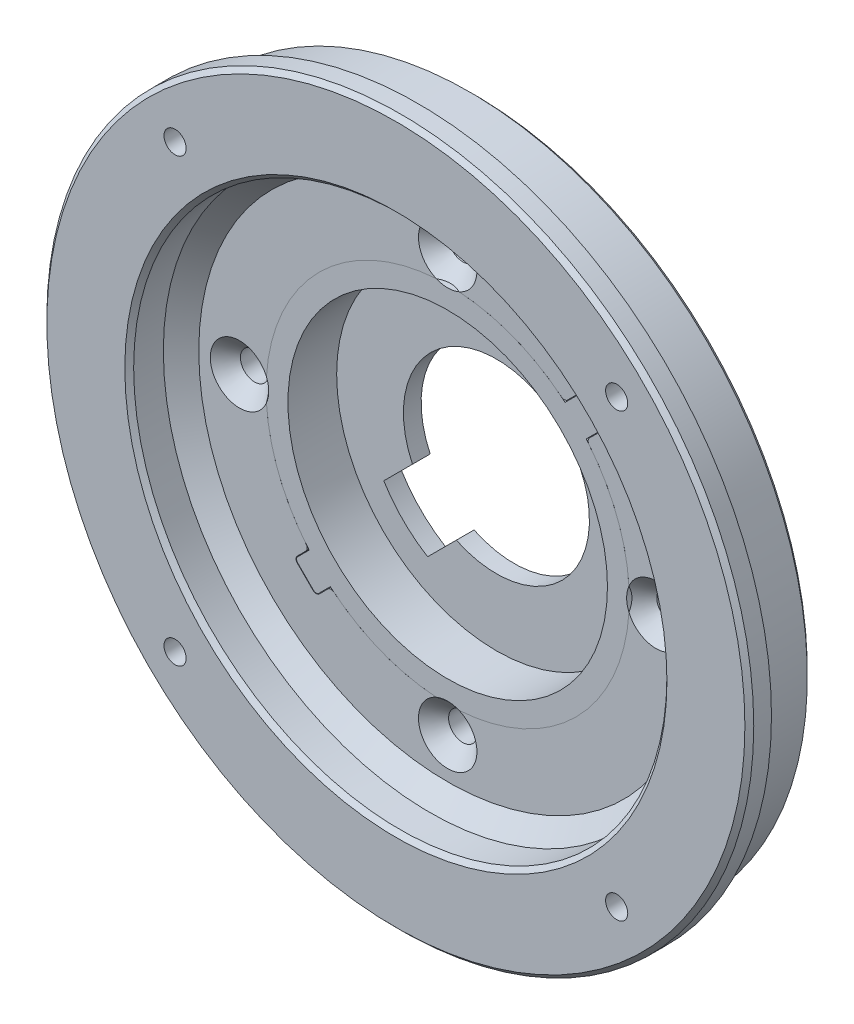
SolidWorks part; units mm, degrees
material "POM 乙缩醛共聚物"
ref_plane "前视基准面" through (0, 0, 0) normal (0, 0, 1) x (1, 0, 0)
ref_plane "上视基准面" through (0, 0, 0) normal (0, 1, 0) x (1, 0, 0)
ref_plane "右视基准面" through (0, 0, 0) normal (1, 0, 0) x (0, 0, -1)
sketch "草图1" plane through (0, 0, 0) normal (0, 0, 1) x (1, 0, 0)
  circle A0 centre (0, 0) radius 30.1
  circle A1 centre (0, 0) radius 38.1
  dimension "D1" = 8
  dimension "D2" = 76.2
extrude "凸台-拉伸1" add sketch "草图1" along normal blind 3.35
sketch "草图2" plane through (0, 0, 3.35) normal (0, 0, 1) x (1, 0, 0)
  circle A0 centre (0, 0) radius 30.1 construction
  circle A1 centre (0, 0) radius 30.1
  circle A2 centre (0, 0) radius 39.9
  circle A3 centre (0, 0) radius 38.1 construction
  dimension "D1" = 1.8
extrude "凸台-拉伸2" add sketch "草图2" along normal blind 2.5
sketch "草图4" plane through (0, 0, 0) normal (0, 0, -1) x (-1, 0, 0)
  circle A0 centre (0, 0) radius 20.5
  circle A1 centre (0, 0) radius 38.1 construction
  circle A2 centre (0, 0) radius 38.1
  dimension "D1" = 41
extrude "凸台-拉伸3" add sketch "草图4" along normal blind 3
chamfer "倒角1" distance 2 angle 45 1 edges at (30.1, 0, 0)
sketch "草图5" plane through (0, 0, 0) normal (0, 0, 1) x (1, 0, 0)
  line L0 (0, 0) -> (-23.5, 0) construction
  circle A0 centre (0, 0) radius 23.5 construction
  circle A1 centre (-23.5, 0) radius 1.5
  circle A2 centre (0, 23.5) radius 1.5
  circle A3 centre (23.5, 0) radius 1.5
  circle A4 centre (0, -23.5) radius 1.5
  point P13 (0, 0)
  dimension "D1" = 47
  dimension "D2" = 3
  dimension "D3" = 4
extrude "切除-拉伸1" cut sketch "草图5" against normal blind 10
chamfer "倒角2" distance 0.5 angle 45 2 edges at (39.9, 0, 5.85) (30.1, 0, 5.85)
sketch "草图6" plane through (0, 0, -3) normal (0, 0, -1) x (-1, 0, 0)
  circle A0 centre (0, 0) radius 20.5 construction
  circle A1 centre (0, 0) radius 20.5
  circle A2 centre (23.5, 0) radius 1.5 construction
  circle A3 centre (0, 23.5) radius 1.5 construction
  circle A4 centre (-23.5, 0) radius 1.5 construction
  circle A5 centre (0, -23.5) radius 1.5 construction
  circle A6 centre (23.5, 0) radius 1.5
  circle A7 centre (0, 23.5) radius 1.5
  circle A8 centre (-23.5, 0) radius 1.5
  circle A9 centre (0, -23.5) radius 1.5
  circle A10 centre (0, 0) radius 29.5
  dimension "D1" = 59
extrude "凸台-拉伸4" add sketch "草图6" along normal blind 5.5
chamfer "倒角3" distance 3 angle 45 1 edges at (-29.5, 0, -3)
chamfer "倒角4" distance 0.5 angle 45 1 edges at (-38.1, 0, -3)
hole_wizard "打孔尺寸(%根据十字)槽半沉头木螺钉的类型1" positions "3D草图1" profile "草图7" countersink size "M3" standard "GB"
sketch3d "3D草图1"
  line L0 (23.5, 0, -8.5) -> (23.5, 0, 0) construction
  line L1 (0, -23.5, -8.5) -> (0, -23.5, 0) construction
  line L2 (-23.5, 0, -8.5) -> (-23.5, 0, 0) construction
  line L3 (0, 23.5, -8.5) -> (0, 23.5, 0) construction
  point P0 (23.5, 0, 0)
  point P4 (0, -23.5, 0)
  point P8 (-23.5, 0, 0)
  point P12 (0, 23.5, 0)
sketch "草图7" plane through (23.5, 0, 0) normal (1, 0, 0) x (0, -1, 0)
  line L0 (0, 0) -> (0, 13.4614)
  line L1 (0, 13.4614) -> (1.6, 12.5)
  line L2 (1.6, 12.5) -> (1.6, 1.7)
  line L3 (1.6, 1.7) -> (3.3, 0)
  line L5 (3.3, 0) -> (0, 0)
  line L6 (-1.6, 1.7) -> (-3.3, 0) construction
  line L10 (0, 13.4614) -> (-1.6, 12.5) construction
  line L11 (0, -6.35) -> (0, 107.95) construction
  dimension "孔直径" = 3.2
  dimension "孔深度" = 12.5
  dimension "近端锥形沉头孔直径" = 6.6
  dimension "近端锥形沉头孔角度" = 90
  dimension "导头角度" = 118
sketch "草图8" plane through (0, 0, -3) normal (0, 0, -1) x (-1, 0, 0)
  line L0 (0, 0) -> (-24.9255, -24.9255) construction
  line L1 (0, 0) -> (0, -35.25) construction
  circle A0 centre (0, 0) radius 35.25 construction
  circle A1 centre (-24.9255, -24.9255) radius 1.2
  circle A2 centre (-24.9255, 24.9255) radius 1.2
  circle A3 centre (24.9255, 24.9255) radius 1.2
  circle A4 centre (24.9255, -24.9255) radius 1.2
  point P14 (0, 0)
  dimension "D1" = 70.5
  dimension "D3" = 2.4
  dimension "D2" = 45
  dimension "D4" = 4
extrude "切除-拉伸2" cut sketch "草图8" against normal blind 10
hole_wizard "M3 螺纹孔1" positions "3D草图2" profile "草图9" tap size "M3" standard "GB"
sketch3d "3D草图2"
  line L0 (24.9255, 24.9255, 5.85) -> (24.9255, 24.9255, -3) construction
  line L1 (24.9255, -24.9255, 5.85) -> (24.9255, -24.9255, -3) construction
  line L2 (-24.9255, -24.9255, 5.85) -> (-24.9255, -24.9255, -3) construction
  line L3 (-24.9255, 24.9255, 5.85) -> (-24.9255, 24.9255, -3) construction
  point P0 (24.9255, 24.9255, 5.85)
  point P4 (24.9255, -24.9255, 5.85)
  point P8 (-24.9255, -24.9255, 5.85)
  point P12 (-24.9255, 24.9255, 5.85)
sketch "草图9" plane through (24.9255, 24.9255, 5.85) normal (1, 0, 0) x (0, -1, 0)
  line L0 (0, 0) -> (0, 13.2511)
  line L1 (0, 13.2511) -> (1.25, 12.5)
  line L2 (1.25, 12.5) -> (1.25, 0)
  line L5 (1.25, 0) -> (0, 0)
  line L10 (0, 13.2511) -> (-1.25, 12.5) construction
  line L11 (0, -6.35) -> (0, 107.95) construction
  dimension "螺纹孔钻头直径" = 2.5
  dimension "螺纹孔钻头深度" = 12.5
  dimension "导头角度" = 118
cosmetic thread "孔螺蚊线1" parameters "D1"=8.85, "D2"=3
cosmetic thread "孔螺蚊线2" parameters "D1"=8.85, "D2"=3
cosmetic thread "孔螺蚊线3" parameters "D1"=8.85, "D2"=3
cosmetic thread "孔螺蚊线4" parameters "D1"=8.85, "D2"=3
sketch "草图12" plane through (0, 0, 0) normal (0, 0, 1) x (1, 0, 0)
  line L0 (-14.4957, -14.4957) -> (14.4957, 14.4957) construction
  line L1 (0, 0) -> (20.5, 0) construction
  line L2 (16.0867, 16.0867) -> (12.9047, 12.9047) construction
  line L3 (17.3241, 14.8492) -> (14.1421, 11.6673)
  line L4 (14.8492, 17.3241) -> (11.6673, 14.1421)
  line L5 (0, 0) -> (14.4957, -14.4957) construction
  line L6 (-16.0867, -16.0867) -> (-12.9047, -12.9047) construction
  line L7 (-14.8492, -17.3241) -> (-11.6673, -14.1421)
  line L8 (-17.3241, -14.8492) -> (-14.1421, -11.6673)
  line L9 (14.8492, 17.3241) -> (17.3241, 14.8492)
  line L10 (-17.3241, -14.8492) -> (-14.8492, -17.3241)
  circle A0 centre (0, 0) radius 20.5 construction
  arc A1 (17.3241, 14.8492) -> (14.8492, 17.3241) centre (16.0867, 16.0867) ccw
  arc A2 (11.6673, 14.1421) -> (14.1421, 11.6673) centre (12.9047, 12.9047) ccw
  arc A3 (-14.8492, -17.3241) -> (-17.3241, -14.8492) centre (-16.0867, -16.0867) cw
  arc A4 (-14.1421, -11.6673) -> (-11.6673, -14.1421) centre (-12.9047, -12.9047) cw
  point P9 (14.4957, 14.4957)
  point P18 (-14.4957, -14.4957)
  dimension "D3" = 1.75
  dimension "D1" = 45
  dimension "D2" = 4.5
extrude "切除-拉伸4" cut sketch "草图12" against normal blind 4.5
fillet "圆角3" radius 0.5 8 edges at (-17.3241, -14.8492, -2.25) (-14.8492, -17.3241, -2.25) (-15.6802, -13.2053, -2.25) (-13.2053, -15.6802, -2.25) (15.6802, 13.2053, -2.25) (13.2053, 15.6802, -2.25) (14.8492, 17.3241, -2.25) (17.3241, 14.8492, -2.25)
sketch "草图13" plane through (0, 0, 0) normal (0, 0, 1) x (1, 0, 0)
  line L54 (-13.5723, -15.9552) -> (-14.5417, -16.9246)
  line L55 (-15.1568, -16.9246) -> (-16.9246, -15.1568)
  line L56 (-16.9246, -14.5417) -> (-15.9552, -13.5723)
  line L57 (-13.2552, -15.6381) -> (-14.5417, -16.9246)
  line L58 (-15.1568, -16.9246) -> (-16.9246, -15.1568)
  line L59 (-16.9246, -14.5417) -> (-15.6381, -13.2552)
  line L69 (15.9552, 13.5723) -> (16.9246, 14.5417)
  line L70 (16.9246, 15.1568) -> (15.1568, 16.9246)
  line L71 (14.5417, 16.9246) -> (13.5723, 15.9552)
  line L72 (15.6381, 13.2552) -> (16.9246, 14.5417)
  line L73 (16.9246, 15.1568) -> (15.1568, 16.9246)
  line L74 (14.5417, 16.9246) -> (13.2552, 15.6381)
  arc A30 (-15.1568, -16.9246) -> (-14.5417, -16.9246) centre (-14.8492, -16.617) ccw
  arc A31 (-16.9246, -14.5417) -> (-16.9246, -15.1568) centre (-16.617, -14.8492) ccw
  arc A32 (-15.1568, -16.9246) -> (-14.5417, -16.9246) centre (-14.8492, -16.617) ccw
  arc A33 (-16.9246, -14.5417) -> (-16.9246, -15.1568) centre (-16.617, -14.8492) ccw
  arc A38 (-15.9654, -12.8591) -> (-12.8591, -15.9654) centre (0, 0) ccw construction
  arc A39 (15.9654, 12.8591) -> (12.8591, 15.9654) centre (0, 0) ccw construction
  arc A40 (16.9246, 14.5417) -> (16.9246, 15.1568) centre (16.617, 14.8492) ccw
  arc A41 (15.1568, 16.9246) -> (14.5417, 16.9246) centre (14.8492, 16.617) ccw
  arc A42 (16.9246, 14.5417) -> (16.9246, 15.1568) centre (16.617, 14.8492) ccw
  arc A43 (15.1568, 16.9246) -> (14.5417, 16.9246) centre (14.8492, 16.617) ccw
  arc A44 (-13.2552, -15.6381) -> (15.6381, 13.2552) centre (0, 0) ccw
  arc A45 (13.2552, 15.6381) -> (-15.6381, -13.2552) centre (0, 0) ccw
  circle A46 centre (0, 0) radius 18.035
  dimension "D3" = 36.07
  dimension "D1" = 0.065
  dimension "D2" = 0.065
extrude "凸台-拉伸5" add sketch "草图13" against normal up to surface (4.5 mm away) separate body up to face at (-15.2626, -15.2626, -4.5)
sketch "草图14" plane through (0, 0, -4.5) normal (0, 0, -1) x (-1, 0, 0)
  circle A0 centre (0, 0) radius 18.035 construction
  circle A1 centre (0, 0) radius 18.035
  circle A2 centre (0, 0) radius 20.4
  dimension "D1" = 40.8
extrude "凸台-拉伸6" add sketch "草图14" along normal blind 2
sketch "草图15" plane through (0, 0, -6.5) normal (0, 0, -1) x (-1, 0, 0)
  circle A0 centre (0, 0) radius 18.035 construction
  circle A1 centre (0, 0) radius 20.4
  circle A2 centre (0, 0) radius 20.4
  circle A3 centre (0, 0) radius 18.035
  dimension "D1" = 0
extrude "凸台-拉伸7" add sketch "草图15" along normal blind 1
sketch "草图16" plane through (0, 0, -7.5) normal (0, 0, -1) x (-1, 0, 0)
  circle A0 centre (0, 0) radius 10.5
  circle A1 centre (0, 0) radius 18.035 construction
  circle A2 centre (0, 0) radius 18.035
  dimension "D1" = 21
extrude "凸台-拉伸8" add sketch "草图16" against normal blind 2
sketch "草图17" plane through (0, 0, 0) normal (0, 0, 1) x (1, 0, 0)
  circle A0 centre (-23.5, 0) radius 3.3
  circle A1 centre (0, -23.5) radius 3.3
  circle A2 centre (0, 23.5) radius 3.3
  circle A3 centre (23.5, 0) radius 3.3
extrude "切除-拉伸5" cut sketch "草图17" against normal blind 14
ref_plane "基准面1" through (0, 0, 0) normal (0.7071, -0.7071, 0) x (0, 0, -1)
sketch "草图18" plane through (0, 0, 0) normal (0.7071, -0.7071, 0) x (0, 0, -1)
  line L1 (0, 18.035) -> (0, -18.035) construction
  line L2 (0, 18.035) -> (0, -18.035) construction
  line L3 (0, 0) -> (2.94, 0) construction
  circle A0 centre (2.94, 0) radius 1.5
  dimension "D1" = 3
  dimension "D2" = 2.94
extrude "切除-拉伸6" cut sketch "草图18" against normal mid plane 80
sketch "草图19" plane through (0, 0, -5.5) normal (0, 0, 1) x (1, 0, 0)
  line L0 (-16.0407, -16.0407) -> (16.0867, 16.0867) construction
  line L1 (-16.9246, -15.1568) -> (-15.1568, -16.9246) construction
  line L2 (15.2028, 16.9706) -> (16.9706, 15.2028) construction
  line L3 (0, 0) -> (-7.4246, 7.4246) construction
  line L4 (-7.7662, -12.716) -> (12.716, 7.7662)
  line L5 (-12.716, -7.7662) -> (7.7662, 12.716)
  line L7 (-13.5658, -18.5156) -> (18.5616, 13.6118) construction
  line L8 (-18.5156, -13.5658) -> (13.6118, 18.5616) construction
  circle A0 centre (0, 0) radius 10.5 construction
  arc A1 (12.716, 7.7662) -> (7.7662, 12.716) centre (0, 0) ccw
  arc A2 (-12.716, -7.7662) -> (-7.7662, -12.716) centre (0, 0) ccw
  dimension "D1" = 29.8
  dimension "D2" = 3.5
  dimension "D3" = 3.5
extrude "切除-拉伸7" cut sketch "草图19" against normal blind 80
